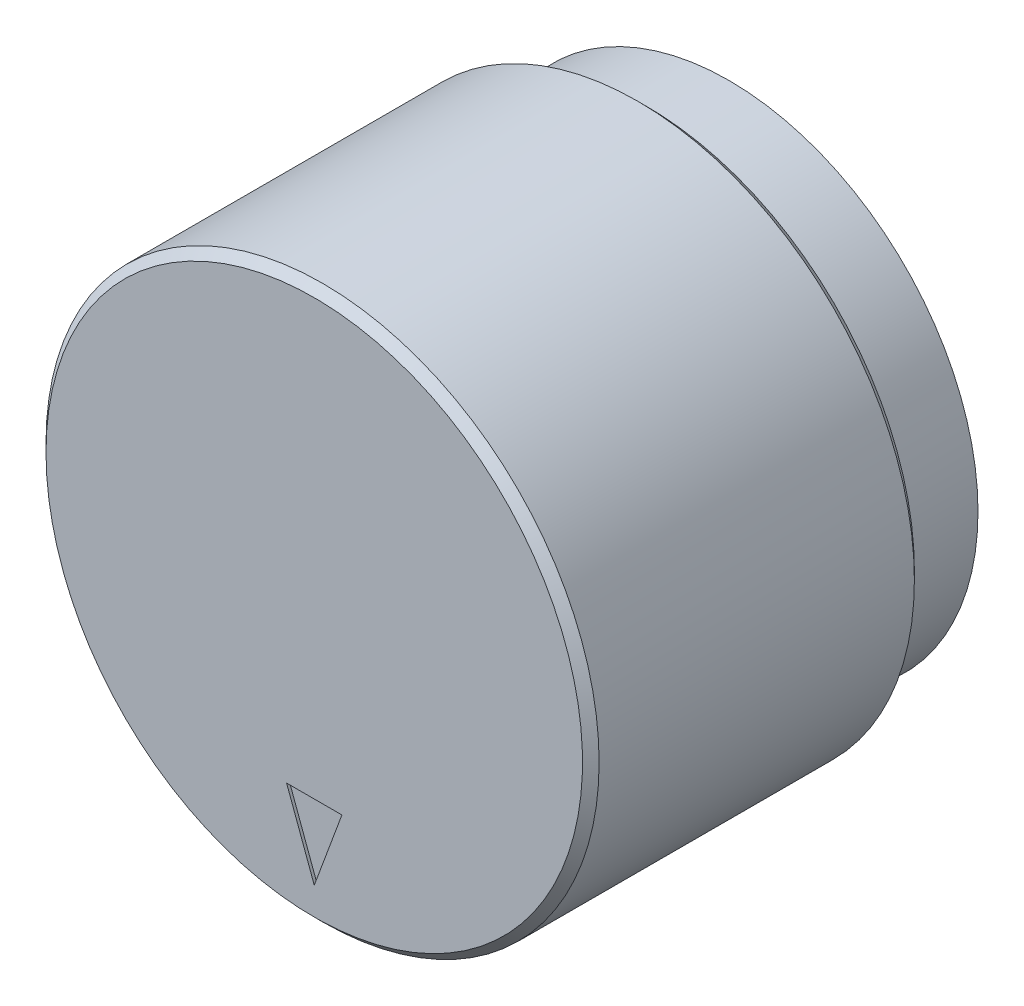
SolidWorks part; units mm, degrees
ref_plane "Front Plane" through (0, 0, 0) normal (1, 0, 0) x (0, 1, 0)
ref_plane "Top Plane" through (0, 0, 0) normal (0, 0, 1) x (0, 1, 0)
ref_plane "Right Plane" through (0, 0, 0) normal (0, 1, 0) x (-1, 0, 0)
sketch "Sketch1" plane through (0, 0, 0) normal (0, 0, 1) x (0, 1, 0)
  circle A0 centre (0, 0) radius 10
  dimension "D1" = 20
extrude "Boss-Extrude1" add sketch "Sketch1" along normal blind 12
sketch "Sketch2" plane through (0, 0, 0) normal (0, 0, -1) x (1, 0, 0)
  circle A0 centre (0, 0) radius 9
  circle A1 centre (0, 0) radius 8
  dimension "D1" = 18
  dimension "D2" = 16
extrude "Boss-Extrude2" add sketch "Sketch2" along normal blind 3
sketch "Sketch3" plane through (0, 0, 0) normal (0, 0, -1) x (1, 0, 0)
  circle A0 centre (0, 0) radius 3
  dimension "D1" = 6
extrude "Cut-Extrude1" cut sketch "Sketch3" against normal blind 10
chamfer "Chamfer1" distance 0.3 angle 45 2 edges at (10, 0, 12) (10, 0, 0)
sketch "Sketch4" plane through (0, 0, 12) normal (0, 0, 1) x (1, 0, 0)
  line L0 (0, 9.7) -> (0, -9.7) construction
  line L1 (-1, -6) -> (1, -6)
  line L2 (-1, -6) -> (0, -8.7)
  line L3 (0, -8.7) -> (1, -6)
  circle A0 centre (0, 0) radius 9.7 construction
  point P7 (0, -6)
  point P8 (0, 0)
  dimension "D1" = 6
  dimension "D2" = 1
  dimension "D3" = 2
extrude "Cut-Extrude2" cut sketch "Sketch4" against normal blind 0.1
